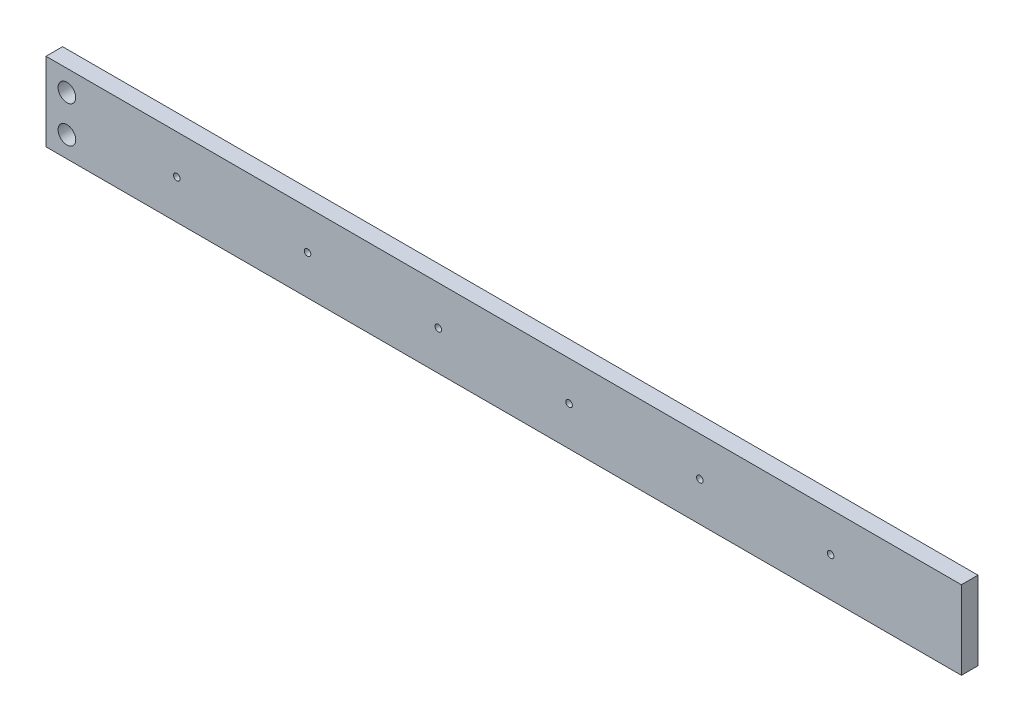
SolidWorks part; units mm, degrees
ref_plane "Front Plane" through (0, 0, 0) normal (0, 0, 1) x (1, 0, 0)
ref_plane "Top Plane" through (0, 0, 0) normal (0, 1, 0) x (1, 0, 0)
ref_plane "Right Plane" through (0, 0, 0) normal (1, 0, 0) x (0, 0, -1)
sketch "Sketch2" plane through (0, 0, 0) normal (0, 0, 1) x (1, 0, 0)
  line L1 (0, 0) -> (350, 0)
  line L2 (0, 0) -> (0, 30)
  line L3 (0, 30) -> (350, 30)
  line L4 (350, 0) -> (350, 30)
  dimension "D1" = 30
  dimension "D2" = 350
extrude "Boss-Extrude1" add sketch "Sketch2" along normal blind 6.35
sketch "Sketch3" plane through (0, 0, 6.35) normal (0, 0, 1) x (1, 0, 0)
  line L0 (8, 30) -> (8, 0) construction
  line L1 (350, 30) -> (0, 30) construction
  line L2 (0, 30) -> (0, 0) construction
  line L3 (0, 0) -> (350, 0) construction
  point P4 (8, 22)
  point P5 (8, 8)
  point P10 (10, 0)
  dimension "D1" = 8
  dimension "D2" = 8
  dimension "D3" = 8
hole_wizard "1/4 Clearance Hole1" positions "Sketch4" profile "Sketch5" hole size "1/4" standard "ANSI Inch" end condition through all
sketch "Sketch4" plane through (0, 0, 6.35) normal (0, 0, 1) x (1, 0, 0)
  point P0 (8, 22)
  point P3 (8, 8)
sketch "Sketch5" plane through (8, 22, 6.35) normal (1, 0, 0) x (0, -1, 0)
  line L0 (0, 0) -> (0, 6.35)
  line L1 (0, 6.35) -> (3.3782, 6.35)
  line L2 (3.3782, 6.35) -> (3.3782, 0)
  line L5 (3.3782, 0) -> (0, 0)
  line L11 (0, -6.35) -> (0, 107.95) construction
  dimension "Thru Hole Dia." = 6.7564
  dimension "Thru Hole Depth" = 6.35
sketch "Sketch6" plane through (0, 0, 6.35) normal (0, 0, 1) x (1, 0, 0)
  line L0 (0, 15) -> (350, 15) construction
  line L1 (0, 30) -> (0, 0) construction
  line L2 (350, 0) -> (350, 30) construction
  point P6 (50, 15)
  dimension "D1" = 50
hole_wizard "Tap Drill for M3x0.5 Tap1" positions "Sketch6" profile "Sketch7" hole size "M3x0.5" standard "ANSI Metric" end condition through all
sketch "Sketch7" plane through (50, 15, 6.35) normal (1, 0, 0) x (0, -1, 0)
  line L0 (0, 0) -> (0, 6.35)
  line L1 (0, 6.35) -> (1.25, 6.35)
  line L2 (1.25, 6.35) -> (1.25, 0)
  line L5 (1.25, 0) -> (0, 0)
  line L11 (0, -6.35) -> (0, 107.95) construction
  dimension "Thru Hole Dia." = 2.5
  dimension "Thru Hole Depth" = 6.35
pattern_linear "LPattern1" count 6 spacing 50 along (1, 0, 0) of "Tap Drill for M3x0.5 Tap1"
